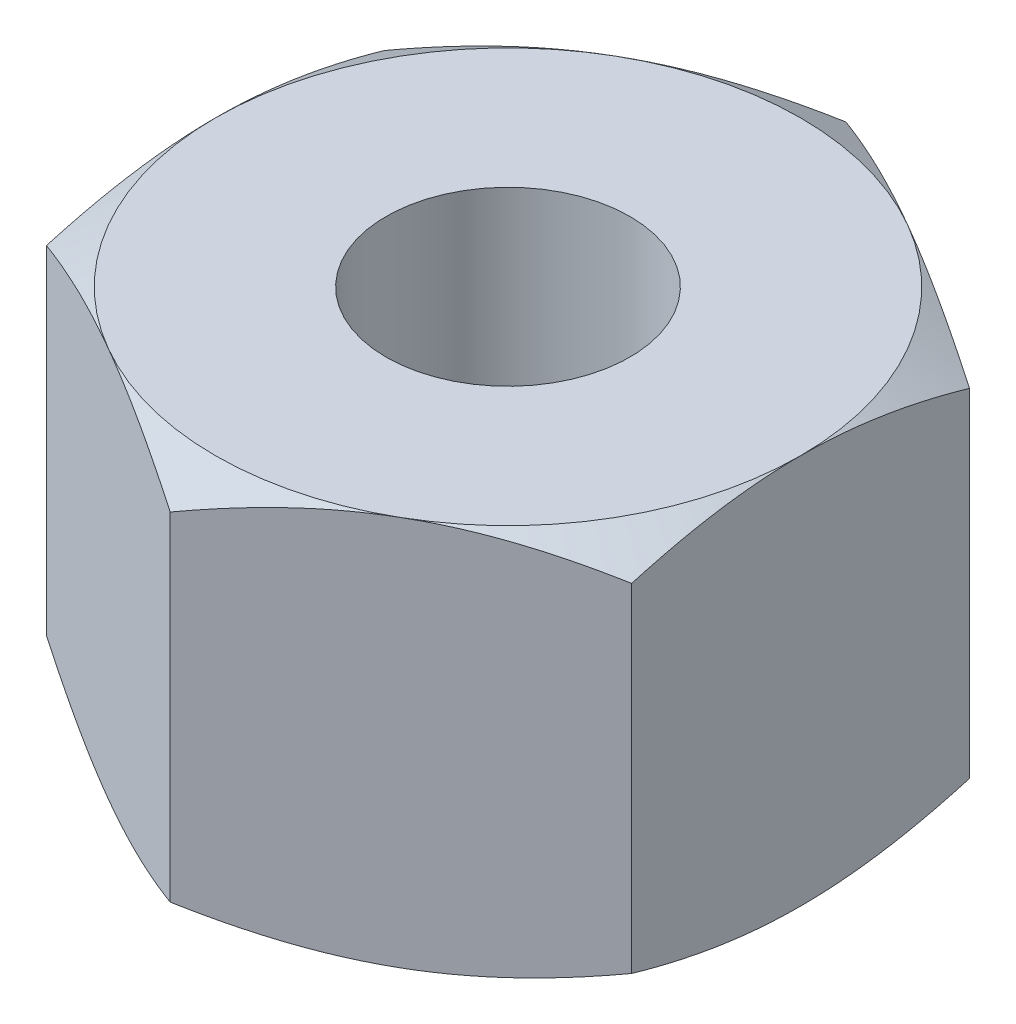
SolidWorks part; units mm, degrees
ref_plane "Front Plane" through (0, 0, 0) normal (0, 0, 1) x (1, 0, 0)
ref_plane "Top Plane" through (0, 0, 0) normal (0, 1, 0) x (1, 0, 0)
ref_plane "Right Plane" through (0, 0, 0) normal (1, 0, 0) x (0, 0, -1)
sketch "Sketch1" plane through (0, 0, 0) normal (0, 1, 0) x (1, 0, 0)
  line L1 (0, 1.7321) -> (-1.5, 0.866)
  line L2 (-1.5, 0.866) -> (-1.5, -0.866)
  line L3 (-1.5, -0.866) -> (0, -1.7321)
  line L4 (0, -1.7321) -> (1.5, -0.866)
  line L5 (1.5, -0.866) -> (1.5, 0.866)
  line L6 (1.5, 0.866) -> (0, 1.7321)
  circle A0 centre (0, 0) radius 0.625
  circle A1 centre (0, 0) radius 1.5 construction
  dimension "D1" = 1.25
  dimension "D2" = 3
extrude "Boss-Extrude1" add sketch "Sketch1" along normal blind 2
sketch "Sketch2" plane through (0, 2, 0) normal (0, 1, 0) x (1, 0, 0)
  circle A0 centre (0, 0) radius 1.5 construction
  circle A1 centre (0, 0) radius 1.5
extrude "Cut-Extrude1" cut sketch "Sketch2" against normal blind 2 draft 60 flip side to cut
sketch "Sketch3" plane through (0, 0, 0) normal (0, -1, 0) x (1, 0, 0)
  circle A0 centre (0, 0) radius 1.5 construction
  circle A1 centre (0, 0) radius 1.5
extrude "Cut-Extrude2" cut sketch "Sketch3" against normal blind 2 draft 60 flip side to cut
